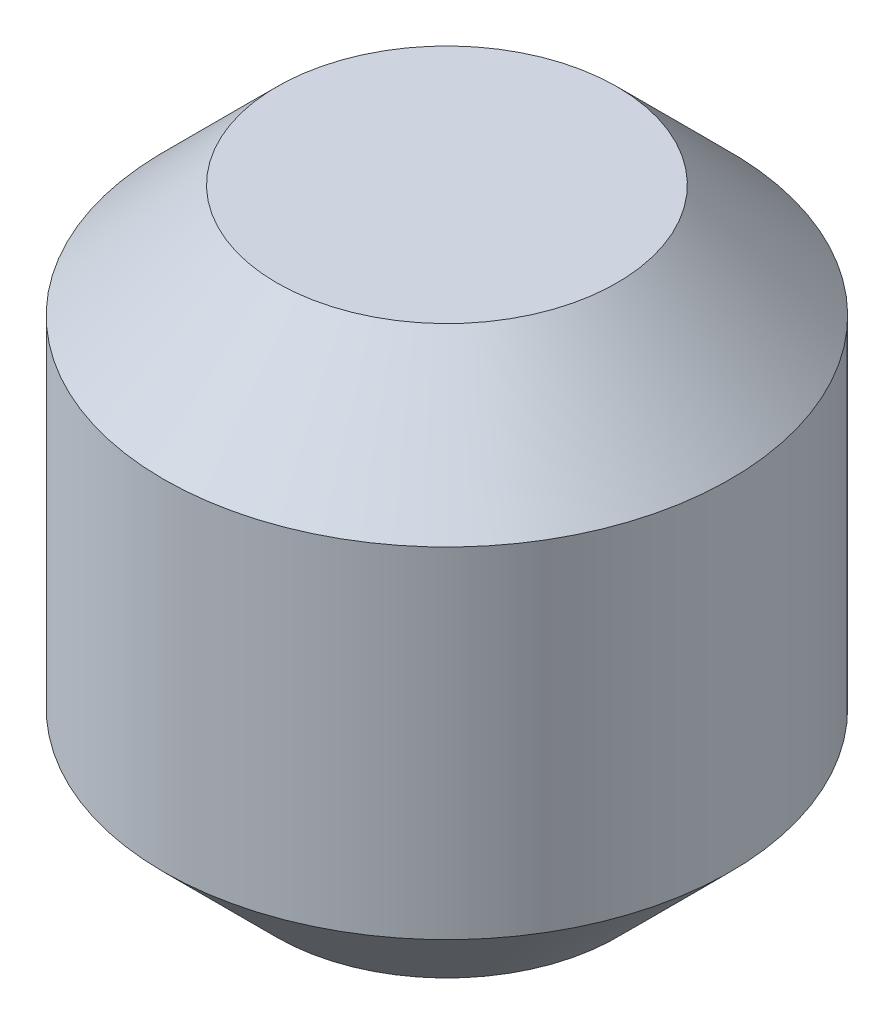
SolidWorks part; units mm, degrees
ref_plane "Front Plane" through (0, 0, 0) normal (0, 0, 1) x (1, 0, 0)
ref_plane "Top Plane" through (0, 0, 0) normal (0, 1, 0) x (1, 0, 0)
ref_plane "Right Plane" through (0, 0, 0) normal (1, 0, 0) x (0, 0, -1)
sketch "Sketch1" plane through (0, 0, 0) normal (0, 1, 0) x (1, 0, 0)
  circle A0 centre (18.9865, -23.4414) radius 25
  point P2 (0, 0)
extrude "Boss-Extrude4" add sketch "Sketch1" along normal blind 50
chamfer "Chamfer2" distance 10 angle 45 1 edges at (18.9865, 50, 48.4414)
chamfer "Chamfer3" distance 10 angle 45 1 edges at (18.9865, 0, 48.4414)
